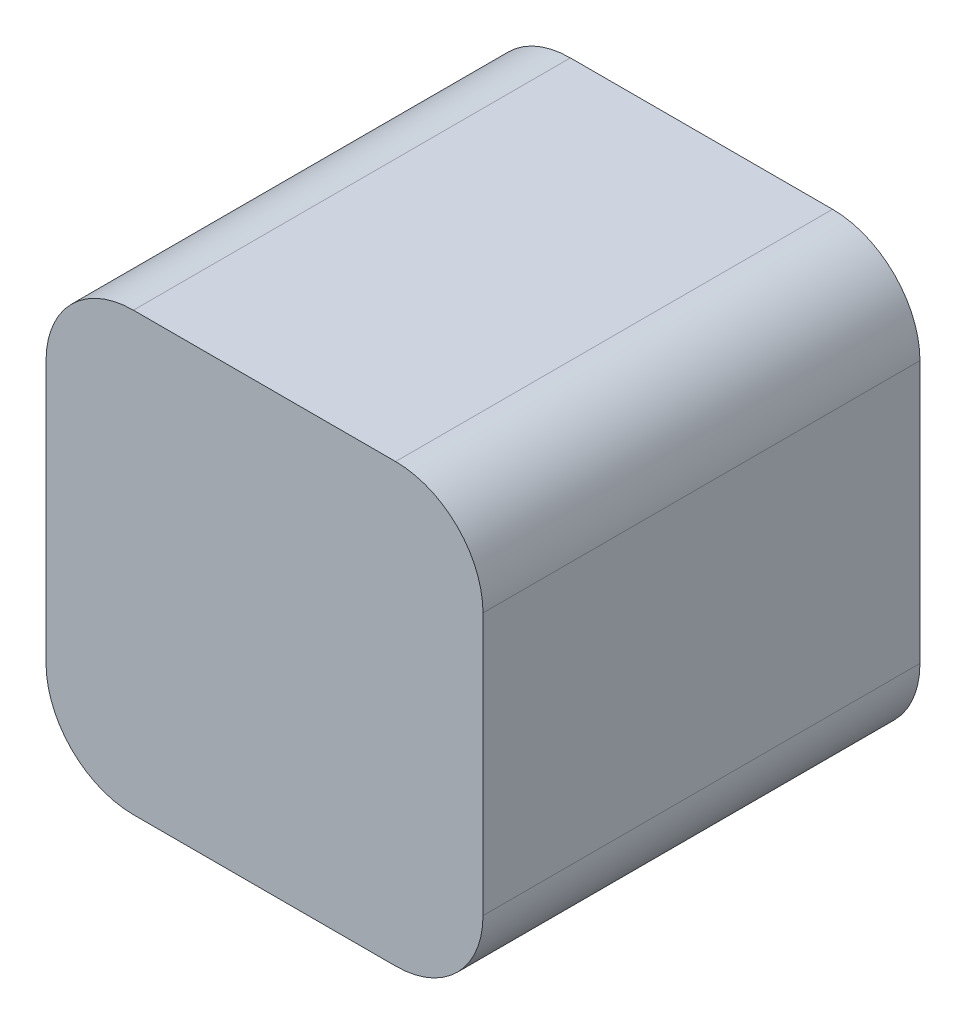
SolidWorks part; units mm, degrees
ref_plane "Alzado" through (0, 0, 0) normal (0, 0, 1) x (1, 0, 0)
ref_plane "Planta" through (0, 0, 0) normal (0, 1, 0) x (1, 0, 0)
ref_plane "Vista lateral" through (0, 0, 0) normal (1, 0, 0) x (0, 0, -1)
sketch "Croquis1" plane through (0, 0, 0) normal (1, 0, 0) x (0, 0, -1)
  line L1 (0, 0) -> (50, 0)
  line L2 (0, 0) -> (0, 50)
  line L3 (0, 50) -> (50, 50)
  line L4 (50, 0) -> (50, 50)
  dimension "D1" = 50
  dimension "D2" = 50
extrude "Saliente-Extruir1" add sketch "Croquis1" along normal blind 50
fillet "Redondeo1" radius 10 4 edges at (50, 50, -25) (50, 0, -25) (0, 0, -25) (0, 50, -25)
